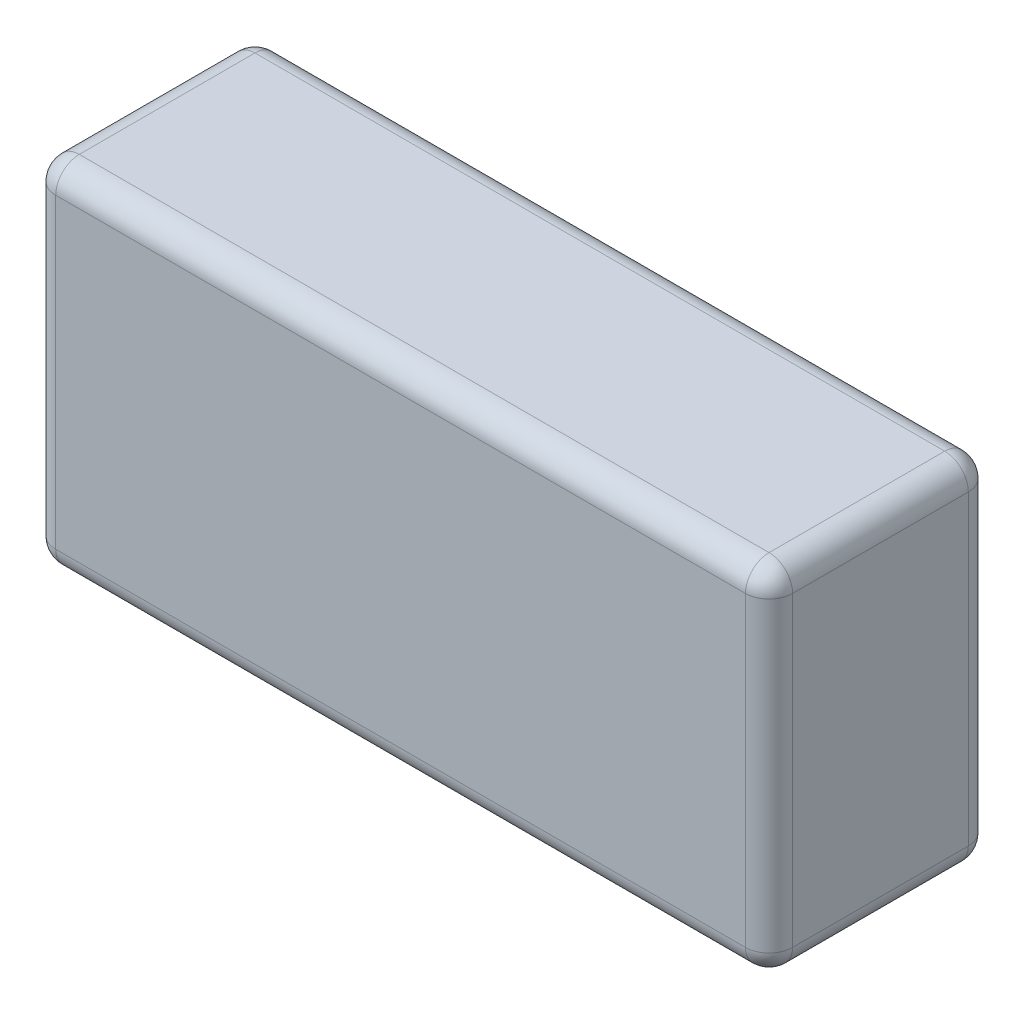
SolidWorks part; units mm, degrees
ref_plane "Front Plane" through (0, 0, 0) normal (0, 0, 1) x (1, 0, 0)
ref_plane "Top Plane" through (0, 0, 0) normal (0, 1, 0) x (1, 0, 0)
ref_plane "Right Plane" through (0, 0, 0) normal (1, 0, 0) x (0, 0, -1)
sketch "Sketch1" plane through (0, 0, 0) normal (0, 0, 1) x (1, 0, 0)
  line L1 (0, 0) -> (62.5, 0)
  line L2 (0, 0) -> (0, 30)
  line L3 (0, 30) -> (62.5, 30)
  line L4 (62.5, 0) -> (62.5, 30)
  dimension "D1" = 62.5
  dimension "D2" = 30
extrude "Boss-Extrude1" add sketch "Sketch1" along normal blind 18.9
fillet "Fillet1" radius 2 12 edges at (0, 30, 9.45) (0, 15, 18.9) (0, 0, 9.45) (0, 15, 0) (62.5, 0, 9.45) (62.5, 15, 18.9) (62.5, 30, 9.45) (62.5, 15, 0) (31.25, 0, 0) (31.25, 0, 18.9) (31.25, 30, 0) (31.25, 30, 18.9)
